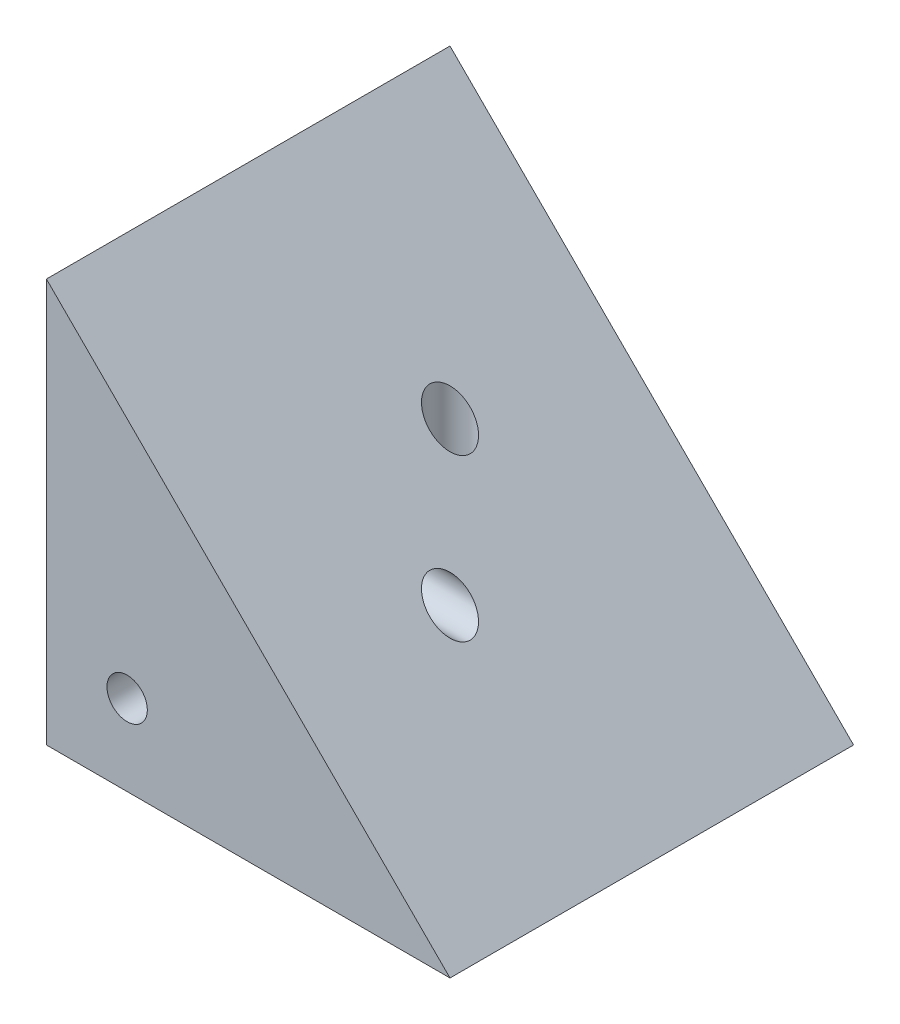
SolidWorks part; units mm, degrees
ref_plane "Спереди" through (0, 0, 0) normal (0, 0, 1) x (1, 0, 0)
ref_plane "Сверху" through (0, 0, 0) normal (0, 1, 0) x (1, 0, 0)
ref_plane "Справа" through (0, 0, 0) normal (1, 0, 0) x (0, 0, -1)
sketch "Эскиз1" plane through (0, 0, 0) normal (0, 0, 1) x (1, 0, 0)
  line L0 (0, 0) -> (0, 25)
  line L1 (0, 25) -> (25, 0)
  line L2 (25, 0) -> (0, 0)
  circle A0 centre (5, 5) radius 1.25
  dimension "D3" = 2.5
  dimension "D4" = 5
  dimension "D1" = 25
  dimension "D2" = 25
  dimension "D5" = 5
extrude "Бобышка-Вытянуть1" add sketch "Эскиз1" along normal blind 25
sketch "Эскиз2" plane through (0, 0, 0) normal (-1, 0, 0) x (0, 0, 1)
  line L0 (25, 0) -> (0, 0) construction
  line L1 (25, 25) -> (25, 0) construction
  circle A0 centre (15, 10) radius 1.25
  dimension "D1" = 2.5
  dimension "D2" = 10
  dimension "D3" = 10
extrude "Вырез-Вытянуть1" cut sketch "Эскиз2" against normal blind 25
sketch "Эскиз3" plane through (0, 0, 0) normal (0, -1, 0) x (1, 0, 0)
  line L0 (0, 0) -> (25, 0) construction
  line L1 (0, 25) -> (0, 0) construction
  circle A0 centre (10, 10) radius 1.25
  dimension "D1" = 2.5
  dimension "D2" = 10
  dimension "D3" = 10
extrude "Вырез-Вытянуть2" cut sketch "Эскиз3" against normal blind 25
